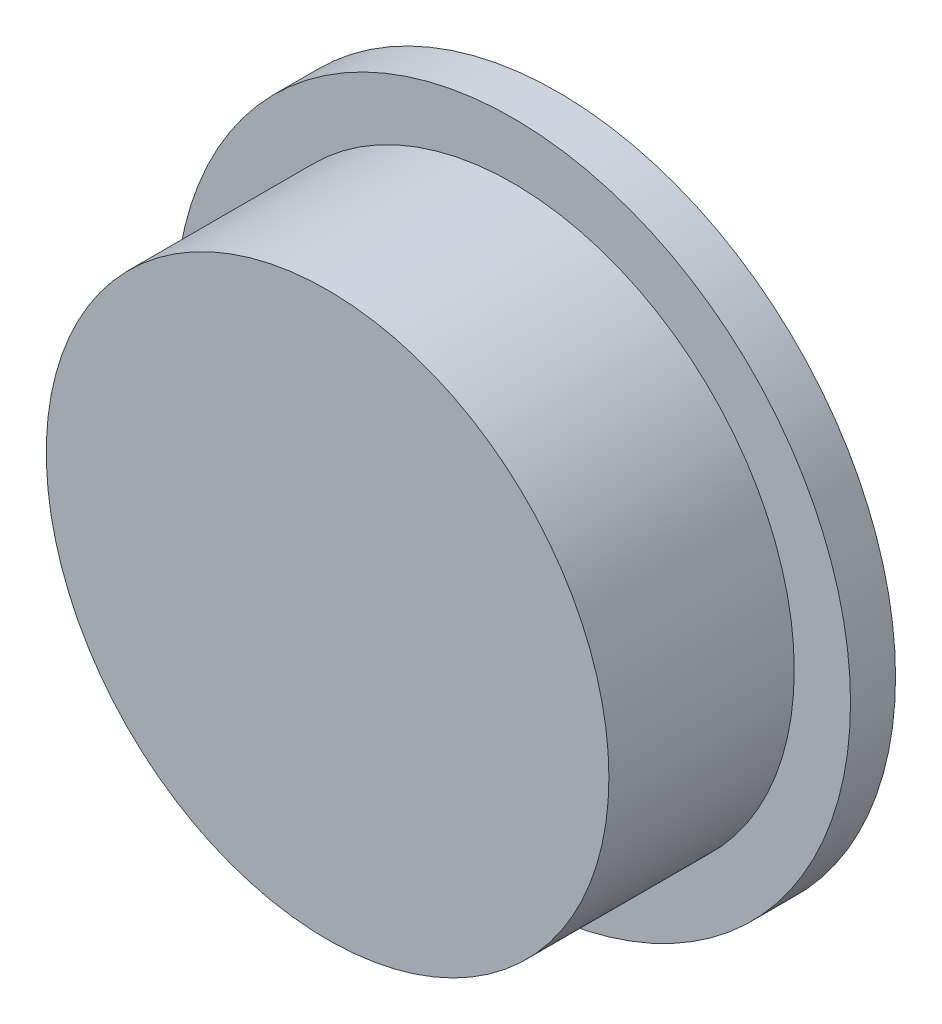
SolidWorks part; units mm, degrees
ref_plane "Front Plane" through (0, 0, 0) normal (0, 0, 1) x (1, 0, 0)
ref_plane "Top Plane" through (0, 0, 0) normal (0, 1, 0) x (1, 0, 0)
ref_plane "Right Plane" through (0, 0, 0) normal (1, 0, 0) x (0, 0, -1)
sketch "Sketch1" plane through (0, 0, 0) normal (0, 0, 1) x (1, 0, 0)
  circle A0 centre (0, 0) radius 7.62
  dimension "D1" = 15.24
extrude "Boss-Extrude1" add sketch "Sketch1" along normal blind 1.016
sketch "Sketch2" plane through (0, 0, 1.016) normal (0, 0, 1) x (1, 0, 0)
  circle A0 centre (0, 0) radius 6.35
  dimension "D1" = 12.7
extrude "Boss-Extrude2" add sketch "Sketch2" along normal blind 4.1834
